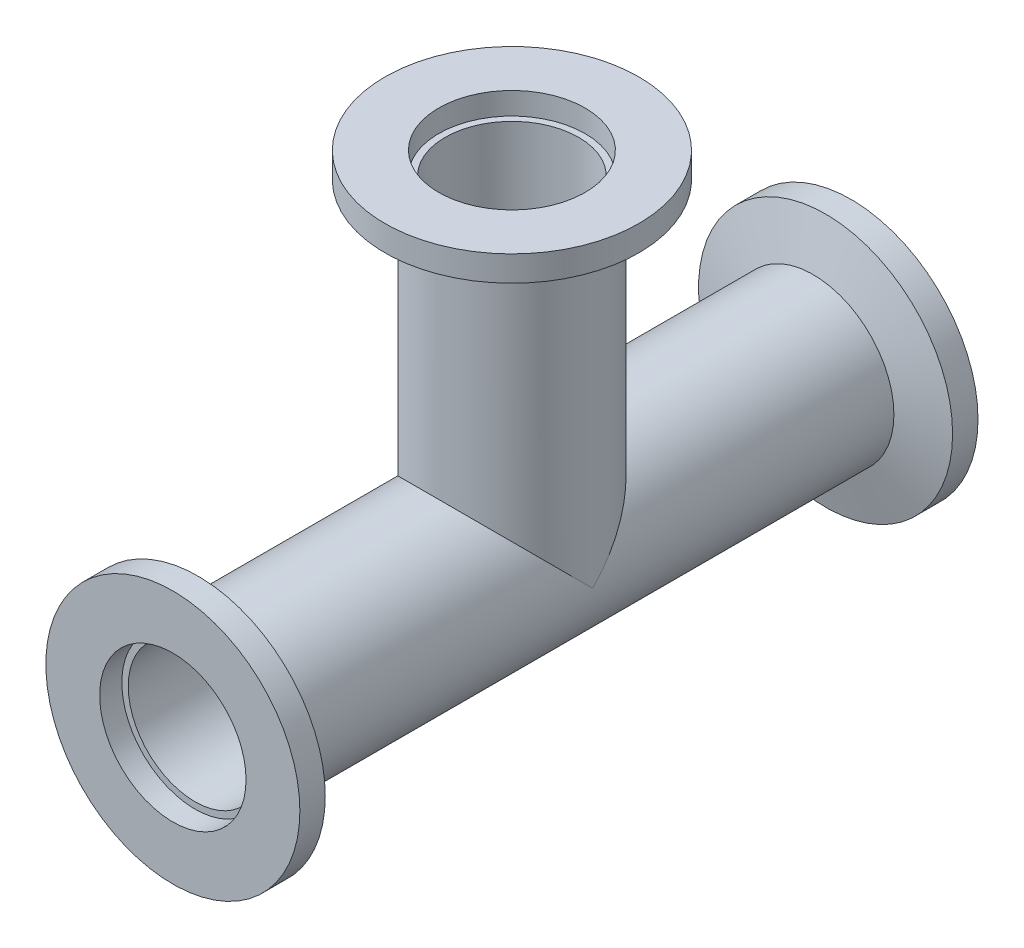
SolidWorks part; units mm, degrees
ref_plane "Front Plane" through (0, 0, 0) normal (0, 0, 1) x (1, 0, 0)
ref_plane "Top Plane" through (0, 0, 0) normal (0, 1, 0) x (1, 0, 0)
ref_plane "Right Plane" through (0, 0, 0) normal (1, 0, 0) x (0, 0, -1)
sketch "Sketch1" plane through (0, 0, 0) normal (1, 0, 0) x (0, 0, -1)
  line L0 (-40.005, -12.5095) -> (0, -12.5095) construction
  line L1 (0, -12.5095) -> (0, 27.4955) construction
  line L2 (-14.986, 27.4955) -> (14.986, 27.4955) construction
  line L3 (-40.005, 2.4765) -> (-40.005, -27.4955) construction
  line L4 (40.005, -27.4955) -> (40.005, 2.4765) construction
  line L5 (-40.005, -27.4955) -> (40.005, 27.4955) construction
  line L6 (0, -12.5095) -> (40.005, -12.5095) construction
  line L7 (-40.005, 2.4765) -> (-37.0078, 2.4765) construction
  line L8 (40.005, -3.8735) -> (37.3888, -3.8735) construction
  line L9 (-40.005, -2.9845) -> (40.005, -2.9845) construction
  line L10 (-40.005, -22.0345) -> (40.005, -22.0345) construction
  point P1 (40.005, -3.8735)
  point P8 (-40.005, -2.9845)
  point P9 (-40.005, -22.0345)
  point P16 (40.005, -21.1455)
  point P17 (-40.005, -4.6355)
  point P20 (-40.005, -20.3835)
  dimension "Flange OD" = 29.972
  dimension "Overall Length" = 80.01
  dimension "For Tube OD" = 19.05
  dimension "Flange Flat Thickness" = 2.9972
  dimension "Connection ID" = 17.272
  dimension "Connection Depth" = 2.6162
  dimension "ID" = 15.748
sketch "Sketch2" plane through (0, 0, 0) normal (1, 0, 0) x (0, 0, -1)
  line L0 (-40.005, 2.4765) -> (-37.0078, 2.4765)
  line L1 (-37.0078, 2.4765) -> (-35.5445, -2.9845)
  line L2 (-35.5445, -2.9845) -> (35.5445, -2.9845)
  line L3 (35.5445, -2.9845) -> (37.0078, 2.4765)
  line L4 (37.0078, 2.4765) -> (40.005, 2.4765)
  line L5 (40.005, 2.4765) -> (40.005, -3.8735)
  line L7 (37.3888, -12.5095) -> (-37.3888, -12.5095)
  line L9 (-40.005, -3.8735) -> (-40.005, 2.4765)
  line L10 (40.005, -3.8735) -> (37.3888, -3.8735)
  line L11 (37.3888, -3.8735) -> (37.3888, -12.5095)
  line L12 (-40.005, -3.8735) -> (-37.3888, -3.8735)
  line L13 (-37.3888, -3.8735) -> (-37.3888, -12.5095)
  line L14 (-40.005, -12.5095) -> (0, -12.5095) construction
  dimension "D1" = 105
revolve "Revolve1" add sketch "Sketch2" angle 360 about L0
sketch "Sketch3" plane through (0, 0, 0) normal (1, 0, 0) x (0, 0, -1)
  line L0 (-14.986, 27.4955) -> (-14.986, 24.4983)
  line L1 (-14.986, 24.4983) -> (-9.525, 23.035)
  line L2 (-9.525, 23.035) -> (-9.525, -12.5095)
  line L3 (-40.005, -12.5095) -> (0, -12.5095) construction
  line L4 (-9.525, -12.5095) -> (0, -12.5095)
  line L5 (0, -12.5095) -> (0, 24.8793)
  line L6 (-14.986, 27.4955) -> (14.986, 27.4955) construction
  line L7 (-14.986, 27.4955) -> (-8.636, 27.4955)
  line L8 (-8.636, 27.4955) -> (-8.636, 24.8793)
  line L9 (-8.636, 24.8793) -> (0, 24.8793)
  line L10 (0, -12.5095) -> (0, 27.4955) construction
  line L11 (0, -12.5095) -> (0, 27.4955) construction
  line L12 (40.005, -3.8735) -> (37.3888, -3.8735) construction
  line L13 (-40.005, 2.4765) -> (-37.0078, 2.4765) construction
  dimension "D1" = 17.272
  dimension "D2" = 105
  dimension "D3" = 19.05
revolve "Revolve2" add sketch "Sketch3" angle 360 about L11
sketch "Sketch4" plane through (0, 0, 0) normal (0, 0, 1) x (1, 0, 0)
  circle A0 centre (0, -12.5095) radius 7.874
extrude "Cut-Extrude1" cut sketch "Sketch4" against normal through all both and the other way through all
sketch "Sketch5" plane through (0, 0, 0) normal (0, 1, 0) x (1, 0, 0)
  circle A0 centre (0, 0) radius 7.874
  dimension "D1" = 15.748
extrude "Cut-Extrude2" cut sketch "Sketch5" along normal through all from vertex at -12.5095 starting at point (0, -12.5095, 0)
equation "\"D1@Sketch3\"=\"Connection ID@Sketch1\""
equation "\"D3@Sketch3\"=\"For Tube OD@Sketch1\""
equation "\"D1@Sketch5\"=\"ID@Sketch1\""
